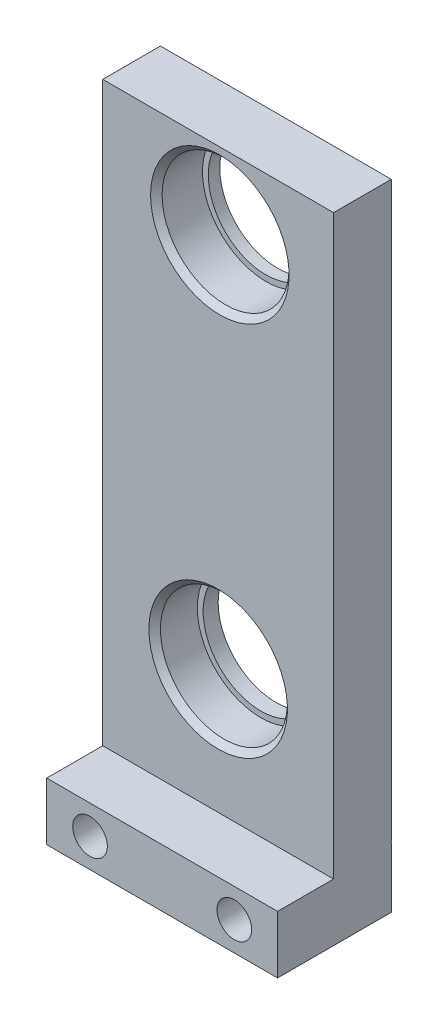
SolidWorks part; units mm, degrees
ref_plane "Ebene vorne" through (0, 0, 0) normal (0, 0, 1) x (1, 0, 0)
ref_plane "Ebene oben" through (0, 0, 0) normal (0, 1, 0) x (1, 0, 0)
ref_plane "Ebene rechts" through (0, 0, 0) normal (1, 0, 0) x (0, 0, -1)
sketch "Skizze1" plane through (0, 0, 0) normal (0, 0, 1) x (1, 0, 0)
  line L1 (0, 0) -> (40, 0)
  line L2 (0, 0) -> (0, 110)
  line L3 (0, 110) -> (40, 110)
  line L4 (40, 0) -> (40, 110)
  dimension "D1" = 40
  dimension "D2" = 110
extrude "Aufsatz-Linear austragen1" add sketch "Skizze1" along normal blind 10
sketch "Skizze2" plane through (0, 0, 0) normal (0, 0, -1) x (-1, 0, 0)
  line L0 (-40, 0) -> (-40, 110) construction
  line L1 (-40, 10.5) -> (0, 10.5)
  line L2 (-40, 10.5) -> (-40, 10.6)
  line L3 (-40, 10.6) -> (0, 10.6)
  line L4 (0, 10.5) -> (0, 10.6)
  line L5 (0, 110) -> (0, 0) construction
  line L6 (0, 0) -> (-40, 0) construction
  dimension "D1" = 10.5
  dimension "D2" = 0.1
extrude "Schnitt-Linear austragen1" cut sketch "Skizze2" against normal blind 0.1
sketch "Skizze3" plane through (0, 0, 0.1) normal (0, 0, -1) x (-1, 0, 0)
  line L0 (-40, 10.6) -> (-40, 10.5) construction
  line L1 (-40, 10.5) -> (0, 10.5) construction
  circle A0 centre (-20, 31.5) radius 11
  dimension "D3" = 22
  dimension "D1" = 20
  dimension "D2" = 21
extrude "Schnitt-Linear austragen2" cut sketch "Skizze3" against normal blind 11
sketch "Skizze4" plane through (0, 0, 0) normal (0, 0, -1) x (-1, 0, 0)
  circle A0 centre (-20.2905, 96.8) radius 11
  circle A1 centre (-20, 31.5) radius 11 construction
  dimension "D1" = 22
  dimension "D2" = 65.3
sketch "Skizze5" plane through (0, 0, 10) normal (0, 0, 1) x (1, 0, 0)
  circle A0 centre (20.2905, 96.8) radius 11
extrude "Schnitt-Linear austragen4" cut sketch "Skizze5" against normal blind 8
sketch "Skizze6" plane through (0, 0, 2) normal (0, 0, 1) x (1, 0, 0)
  circle A0 centre (20.2905, 96.8) radius 10
extrude "Schnitt-Linear austragen5" cut sketch "Skizze6" against normal blind 8
chamfer "Fase1" distance 1 angle 45 2 edges at (9, 31.5, 10) (31.2905, 96.8, 10)
sketch "Skizze7" plane through (0, 0, 10) normal (0, 0, 1) x (1, 0, 0)
  circle A0 centre (20, 31.5) radius 14.681
  dimension "D1" = 29.362
sketch "Skizze8" plane through (0, 0, 10) normal (0, 0, 1) x (1, 0, 0)
  circle A0 centre (20.2905, 96.8) radius 53.1
  dimension "D1" = 106.2
sketch "Skizze10" plane through (0, 0, 10) normal (0, 0, 1) x (1, 0, 0)
  line L0 (40, 0) -> (40, 110) construction
  line L1 (0, 0) -> (40, 0)
  line L2 (0, 0) -> (0, 10)
  line L3 (0, 10) -> (40, 10)
  line L4 (40, 0) -> (40, 10)
  dimension "D1" = 10
extrude "Aufsatz-Linear austragen2" add sketch "Skizze10" along normal blind 9.7
sketch "Skizze11" plane through (0, 0, 0) normal (0, 0, -1) x (-1, 0, 0)
  line L0 (-40, 10.5) -> (0, 10.5) construction
  line L1 (-40, 10.5) -> (0, 10.5) construction
  line L2 (0, 10.5) -> (0, 0) construction
  line L3 (-40, 0) -> (-40, 10.5) construction
  circle A0 centre (-32.5, 5) radius 3
  circle A1 centre (-7.5, 5) radius 3
  dimension "D1" = 6
  dimension "D2" = 6
  dimension "D3" = 5.5
  dimension "D4" = 5.5
  dimension "D5" = 7.5
  dimension "D6" = 7.5
extrude "Schnitt-Linear austragen6" cut sketch "Skizze11" against normal blind 21
sketch "Skizze12" plane through (0, 0, 0) normal (0, 0, -1) x (-1, 0, 0)
  circle A0 centre (-32.5, 5) radius 4.5
  circle A1 centre (-7.5, 5) radius 4.5
  dimension "D1" = 9
  dimension "D2" = 9
sketch "Skizze13" plane through (0, 0, 0.1) normal (0, 0, -1) x (-1, 0, 0)
  circle A0 centre (-20, 31.5) radius 10
  dimension "D1" = 20
extrude "Schnitt-Linear austragen11" cut sketch "Skizze12" against normal blind 13
sketch "Skizze15" plane through (0, 0, 0.1) normal (0, 0, 1) x (1, 0, 0)
  circle A0 centre (20, 31.5) radius 15.6757
extrude "Aufsatz-Linear austragen3" add sketch "Skizze15" along normal blind 2.5
extrude "Schnitt-Linear austragen13" cut sketch "Skizze13" against normal blind 15 and the other way blind 3 contours A0
